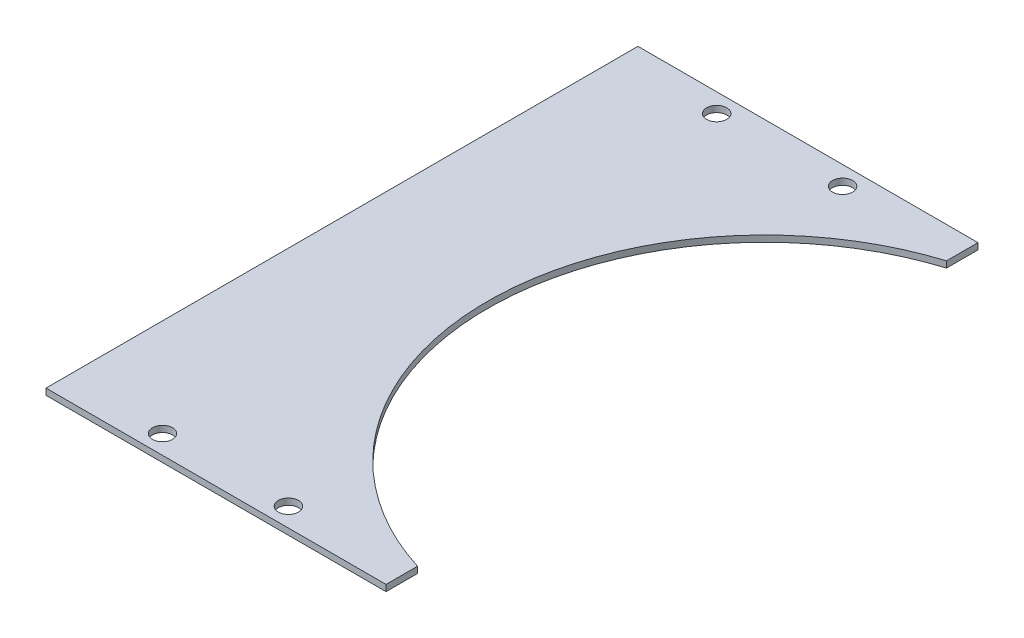
SolidWorks part; units mm, degrees
material "环氧树脂FR-4"
ref_plane "前视基准面" through (0, 0, 0) normal (0, 0, 1) x (1, 0, 0)
ref_plane "上视基准面" through (0, 0, 0) normal (0, 1, 0) x (1, 0, 0)
ref_plane "右视基准面" through (0, 0, 0) normal (1, 0, 0) x (0, 0, -1)
sketch "草图2" plane through (0, 0, 0) normal (0, 1, 0) x (1, 0, 0)
  line L0 (0, -47) -> (0, 47)
  line L1 (0, 47) -> (54, 47)
  line L3 (54, 42) -> (54, -42) construction
  line L6 (54, 47) -> (54, 42)
  line L8 (54, -42) -> (54, -47)
  line L9 (54, -47) -> (0, -47)
  arc A5 (54, 42) -> (54, -42) centre (67.1149, 0) ccw
  point P4 (0, 0)
  dimension "D3" = 47
  dimension "D4" = 5
  dimension "D5" = 44
  dimension "D1" = 94
  dimension "D2" = 54
extrude "凸台-拉伸1" add sketch "草图2" along normal blind 1
sketch "草图3" plane through (0, 1, 0) normal (0, 1, 0) x (1, 0, 0)
  line L0 (15.5, 44) -> (35.5, 44) construction
  line L1 (0, 0) -> (23.1149, 0) construction
  line L2 (0, 47) -> (0, -47) construction
  line L3 (54, 47) -> (0, 47) construction
  circle A0 centre (15.5, 44) radius 1.6
  circle A1 centre (35.5, 44) radius 1.6
  arc A2 (54, 42) -> (54, -42) centre (67.1149, 0) ccw construction
  circle A3 centre (15.5, -44) radius 1.6
  circle A4 centre (35.5, -44) radius 1.6
  dimension "D2" = 3.2
  dimension "D1" = 20
  dimension "D3" = 15.5
  dimension "D4" = 3
extrude "切除-拉伸1" cut sketch "草图3" against normal blind 10
